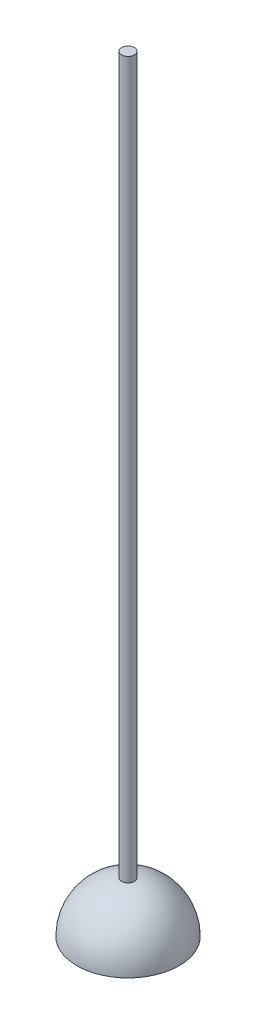
SolidWorks part; units mm, degrees
material "ABS"
ref_plane "前视基准面" through (0, 0, 0) normal (0, 0, 1) x (1, 0, 0)
ref_plane "上视基准面" through (0, 0, 0) normal (0, 1, 0) x (1, 0, 0)
ref_plane "右视基准面" through (0, 0, 0) normal (1, 0, 0) x (0, 0, -1)
sketch "草图2" plane through (0, 0, 0) normal (0, 0, 1) x (1, 0, 0)
  line L0 (0, 0) -> (-100, 0)
  line L1 (0, 0) -> (0, 100)
  arc A0 (0, 100) -> (-100, 0) centre (0, 0) ccw
  dimension "D1" = 200
revolve "旋转1" add sketch "草图2" angle 360 about L1
sketch "草图3" plane through (0, 0, 0) normal (0, -1, 0) x (1, 0, 0)
  circle A0 centre (0, 0) radius 12.5
  dimension "D1" = 25
extrude "凸台-拉伸1" add sketch "草图3" against normal blind 1500
